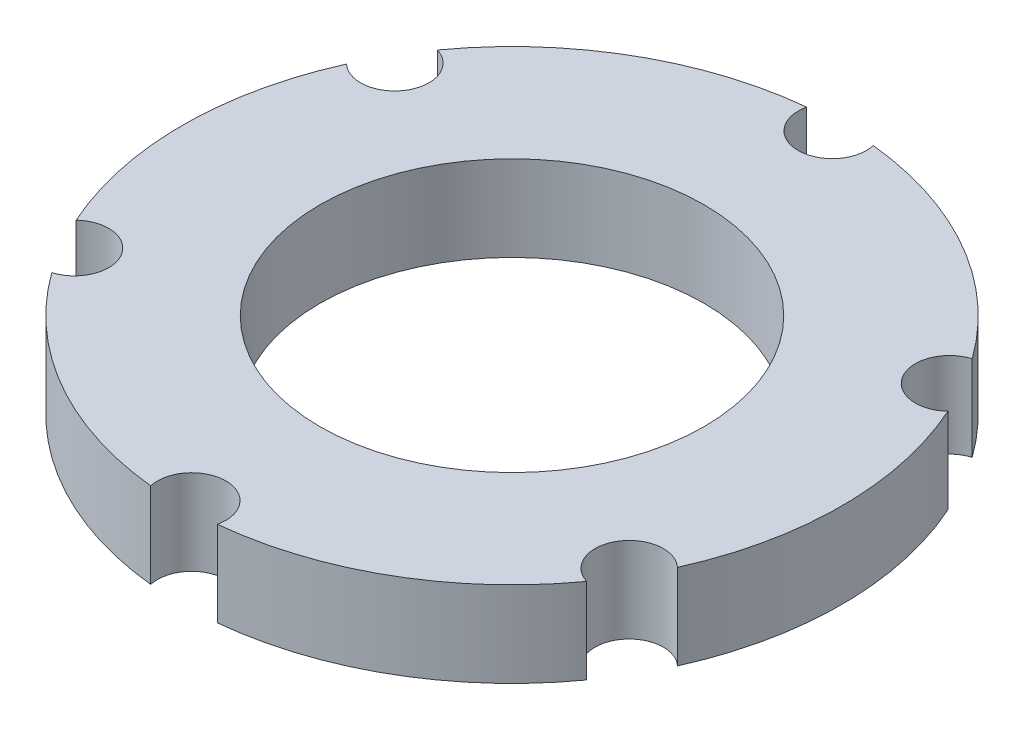
SolidWorks part; units mm, degrees
ref_plane "Front Plane" through (0, 0, 0) normal (0, 0, 1) x (1, 0, 0)
ref_plane "Top Plane" through (0, 0, 0) normal (0, 1, 0) x (1, 0, 0)
ref_plane "Right Plane" through (0, 0, 0) normal (1, 0, 0) x (0, 0, -1)
sketch "Sketch1" plane through (0, 0, 0) normal (0, 1, 0) x (1, 0, 0)
  circle A0 centre (0, 0) radius 30.861
  circle A1 centre (0, 0) radius 14.2875
  dimension "D1" = 61.722
  dimension "D2" = 28.575
extrude "Boss-Extrude1" add sketch "Sketch1" along normal blind 6.35
sketch "Sketch2" plane through (0, 6.35, 0) normal (0, 1, 0) x (1, 0, 0)
  circle A1 centre (0, 23.8125) radius 2.54
  circle A2 centre (0, -23.8125) radius 2.54
  circle A3 centre (20.6222, 11.9062) radius 2.54
  circle A4 centre (20.6222, -11.9062) radius 2.54
  circle A5 centre (-20.6222, 11.9063) radius 2.54
  circle A6 centre (-20.6222, -11.9062) radius 2.54
  dimension "D1" = 5.08
  dimension "D2" = 23.8125
  dimension "D3" = 23.8125
  dimension "D4" = 23.8125
  dimension "D5" = 23.8125
  dimension "D6" = 23.8125
  dimension "D7" = 23.8125
  dimension "D8" = 23.8125
extrude "Cut-Extrude1" cut sketch "Sketch2" against normal up to surface (6.35 mm away) up to face at (0, 0, 30.861)
sketch "Sketch3" plane through (0, 6.35, 0) normal (0, 1, 0) x (1, 0, 0)
  circle A0 centre (0, 0) radius 30.861
  circle A1 centre (0, 0) radius 24.511
  circle A2 centre (0, 0) radius 30.861 construction
  dimension "D1" = 6.35
extrude "Cut-Extrude2" cut sketch "Sketch3" against normal through all
equation "\"D3@Sketch2\"=\"D2@Sketch2\""
equation "\"D4@Sketch2\"=\"D2@Sketch2\""
equation "\"D5@Sketch2\"=\"D2@Sketch2\""
equation "\"D6@Sketch2\"=\"D2@Sketch2\""
equation "\"D7@Sketch2\"=\"D2@Sketch2\""
